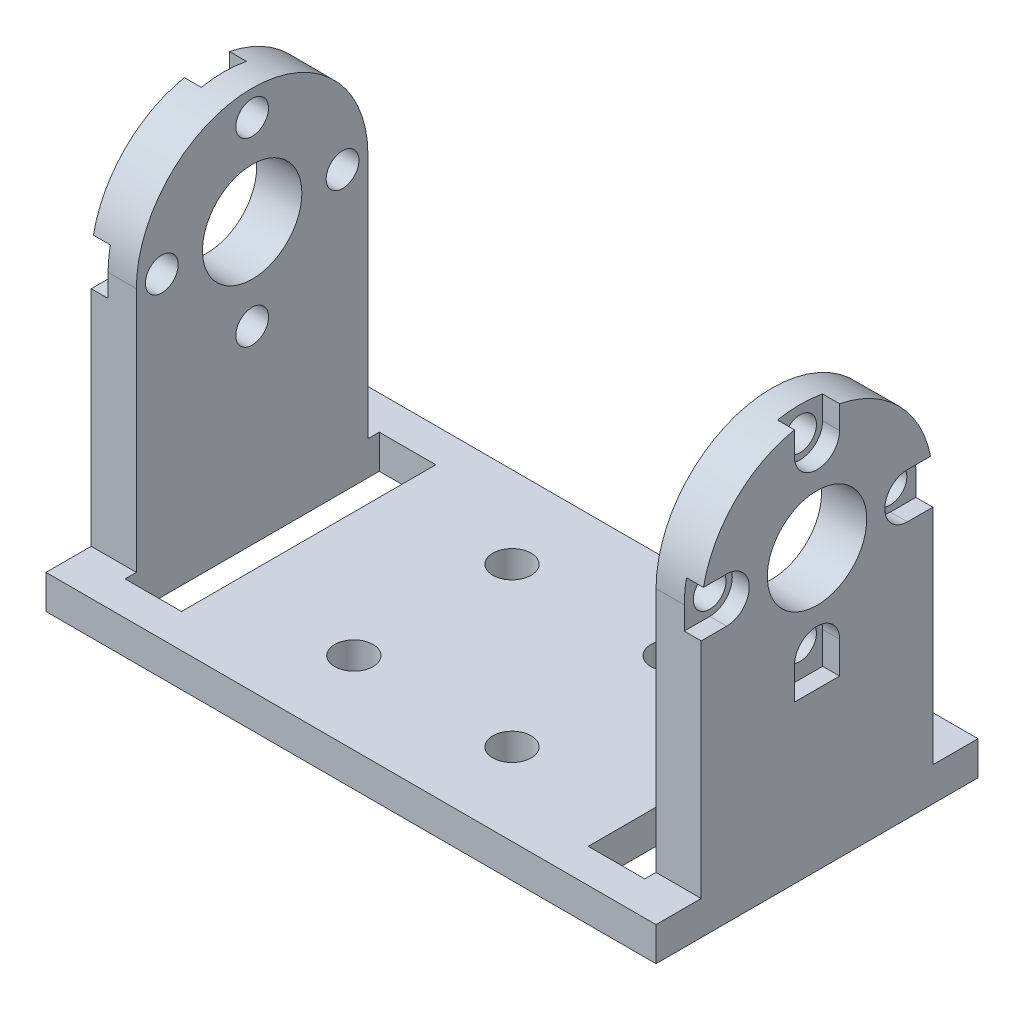
SolidWorks part; units mm, degrees
ref_plane "Front Plane" through (0, 0, 0) normal (0, 0, 1) x (1, 0, 0)
ref_plane "Top Plane" through (0, 0, 0) normal (0, 1, 0) x (1, 0, 0)
ref_plane "Right Plane" through (0, 0, 0) normal (1, 0, 0) x (0, 0, -1)
sketch "Sketch1" plane through (0, 0, 0) normal (0, 1, 0) x (1, 0, 0)
  line L0 (0, 0) -> (0, -7.6155) construction
  line L1 (-18, 14.25) -> (18, 14.25)
  line L2 (-18, 14.25) -> (-18, -14.25)
  line L3 (-18, -14.25) -> (18, -14.25)
  line L4 (18, 14.25) -> (18, -14.25)
  line L5 (0, 0) -> (0, 12.9892) construction
  line L6 (-18, 14.25) -> (-27, 14.25)
  line L7 (-18, 14.25) -> (-18, -14.25)
  line L8 (-18, -14.25) -> (-27, -14.25)
  line L9 (-27, 14.25) -> (-27, -14.25)
  line L10 (18, 14.25) -> (27, 14.25)
  line L11 (18, 14.25) -> (18, -14.25)
  line L12 (18, -14.25) -> (27, -14.25)
  line L13 (27, 14.25) -> (27, -14.25)
  line L14 (-23, 11.25) -> (-18, 11.25)
  line L15 (-23, 11.25) -> (-23, -11.25)
  line L16 (-23, -11.25) -> (-18, -11.25)
  line L17 (-18, 11.25) -> (-18, -11.25)
  line L18 (18, 11.25) -> (18, -11.25)
  line L19 (23, -11.25) -> (18, -11.25)
  line L20 (23, 11.25) -> (23, -11.25)
  line L21 (23, 11.25) -> (18, 11.25)
  circle A0 centre (0, 0) radius 7.5
  circle A1 centre (-9, 8.25) radius 1.7
  circle A2 centre (-9, -8.25) radius 1.7
  circle A3 centre (9, -8.25) radius 1.7
  circle A4 centre (9, 8.25) radius 1.7
  point P0 (0, 0)
  dimension "D3" = 9
  dimension "D4" = 8.25
  dimension "D5" = 8.25
  dimension "D6" = 9
  dimension "D7" = 9
  dimension "D9" = 15
  dimension "D14" = 3.4
  dimension "D1" = 36
  dimension "D2" = 28.5
  dimension "D8" = 9
  dimension "D10" = 4
  dimension "D11" = 3
  dimension "D12" = 3
  dimension "D13" = 5
extrude "Boss-Extrude2" add sketch "Sketch1" along normal blind 3
sketch "Sketch2" plane through (0, 3, 0) normal (0, 1, 0) x (1, 0, 0)
  line L5 (27, 14.25) -> (27, -14.25) construction
  line L6 (27, 10.25) -> (23, 10.25)
  line L7 (27, 10.25) -> (27, -10.25)
  line L8 (27, -10.25) -> (23, -10.25)
  line L9 (23, 10.25) -> (23, -10.25)
  line L10 (27, 14.25) -> (-27, 14.25) construction
  dimension "D1" = 4
  dimension "D2" = 20.5
  dimension "D3" = 4
extrude "Boss-Extrude3" add sketch "Sketch2" along normal blind 21.75
sketch "Sketch4" plane through (27, 0, 0) normal (1, 0, 0) x (0, 0, -1)
  line L0 (-10.25, 24.75) -> (10.25, 24.75) construction
  circle A0 centre (0, 24.75) radius 10.25
  point P18 (0, 17.75)
extrude "Boss-Extrude4" add sketch "Sketch4" against normal blind 4
ref_plane "Plane1" through (0, 0, 0) normal (1, 0, 0) x (0, 0, -1)
mirror "Mirror1" about plane through (0, 0, 0) normal (1, 0, 0) of "Boss-Extrude3", "Boss-Extrude4"
sketch "Sketch6" plane through (27, 0, 0) normal (1, 0, 0) x (0, 0, -1)
  line L0 (-10.25, 24.75) -> (10.25, 24.75) construction
  line L1 (0, 35) -> (0, 14.5) construction
  circle A6 centre (0, 24.75) radius 4.4
  circle A7 centre (0, 24.75) radius 8
  circle A8 centre (0, 32.75) radius 1.45
  circle A9 centre (8, 24.75) radius 1.45
  circle A10 centre (0, 16.75) radius 1.45
  circle A11 centre (-8, 24.75) radius 1.45
  circle A12 centre (0, 24.75) radius 10.25
  point P21 (0, 24.75)
  dimension "D1" = 8.8
  dimension "D2" = 16
  dimension "D3" = 4
  dimension "D4" = 2.9
extrude "Cut-Extrude3" cut sketch "Sketch6" against normal blind 4 contours A6 | A7 A11 | A7 A11 | A7 A10 | A7 A10 | A7 A9 | A7 A9 | A7 A8 | A7 A8
mirror "Mirror3" about plane through (0, 0, 0) normal (1, 0, 0) of "Cut-Extrude3"
sketch "Sketch7" plane through (27, 0, 0) normal (1, 0, 0) x (0, 0, -1)
  line L0 (10.8224, 26.75) -> (10.8224, 22.75)
  line L2 (-2, 32.75) -> (-2, 35.5724)
  line L3 (-2, 35.5724) -> (2, 35.5724)
  line L4 (2, 32.75) -> (2, 35.5724)
  line L5 (8, 22.75) -> (10.8224, 22.75)
  line L6 (8, 26.75) -> (10.8224, 26.75)
  line L7 (2, 13.9276) -> (-2, 13.9276)
  line L8 (-2, 16.75) -> (-2, 13.9276)
  line L9 (2, 16.75) -> (2, 13.9276)
  line L10 (-10.8224, 22.75) -> (-10.8224, 26.75)
  line L11 (-8, 26.75) -> (-10.8224, 26.75)
  line L12 (-8, 22.75) -> (-10.8224, 22.75)
  circle A0 centre (0, 32.75) radius 2
  circle A1 centre (0, 24.75) radius 8
  circle A2 centre (8, 24.75) radius 2
  circle A3 centre (0, 16.75) radius 2
  circle A4 centre (-8, 24.75) radius 2
  point P15 (0, 24.75)
  point P32 (0, 24.75)
  circle M1 centre (-8, 24.75) radius 1.45
  circle M2 centre (0, 16.75) radius 1.45
  circle M3 centre (8, 24.75) radius 1.45
  circle M4 centre (0, 32.75) radius 1.45
  line M6 (10.25, 3) -> (10.25, 24.75)
  arc M7 (10.25, 24.75) -> (-10.25, 24.75) centre (0, 24.75) ccw
  line M8 (-10.25, 24.75) -> (-10.25, 3)
  dimension "D1" = 4
  dimension "D3" = 4
  dimension "D2" = 4
  dimension "D4" = 4
extrude "Cut-Extrude4" cut sketch "Sketch7" against normal blind 1.5 contours A1 M1 | A1 M1 | A1 A0 M4 | A0 A1 M4 | A1 A2 M3 | A1 A2 M3 | A1 A3 M2 | A1 A3 M2 | L4 L3 L2 M7 | A0 L4 L2 M7 | A2 L5 L6 M6 M7 | A3 L8 L7 L9 | A4 L11 L12 M7 M8
mirror "Mirror4" about plane through (0, 0, 0) normal (1, 0, 0) of "Cut-Extrude4"
sketch "Sketch8" plane through (0, 3, 0) normal (0, 1, 0) x (1, 0, 0)
  line L0 (27, -14.25) -> (-27, -14.25) construction
  line L1 (-14.3907, 14.25) -> (14.3907, 14.25)
  line L2 (-14.3907, 14.25) -> (-14.3907, -14.25)
  line L3 (-14.3907, -14.25) -> (14.3907, -14.25)
  line L4 (14.3907, 14.25) -> (14.3907, -14.25)
  line L5 (-14.3907, 14.25) -> (14.3907, -14.25) construction
  line L6 (-14.3907, -14.25) -> (14.3907, 14.25) construction
  point P0 (0, 0)
extrude "Boss-Extrude5" add sketch "Sketch8" against normal blind 3
sketch "Sketch9" plane through (0, 3, 0) normal (0, 1, 0) x (1, 0, 0)
  line L3 (-7, 7) -> (7, 7)
  line L4 (-7, 7) -> (-7, -7)
  line L5 (-7, -7) -> (7, -7)
  line L6 (7, 7) -> (7, -7)
  line L7 (-7, 7) -> (7, -7) construction
  line L8 (-7, -7) -> (7, 7) construction
  circle A0 centre (0, 0) radius 5
  circle A2 centre (-7, 7) radius 1.7
  circle A3 centre (7, 7) radius 1.7
  circle A4 centre (7, -7) radius 1.7
  circle A5 centre (-7, -7) radius 1.7
  dimension "D1" = 14
  dimension "D2" = 14
  dimension "D3" = 10
  dimension "D4" = 3.4
  dimension "D5" = 2
  dimension "D6" = 2
extrude "Cut-Extrude5" cut sketch "Sketch9" against normal blind 3 contours L4 A5 L5 | L5 A4 L6 | L6 A3 L3 | L3 A3 L6 | L5 A5 L4 | L6 A4 L5 | A2
